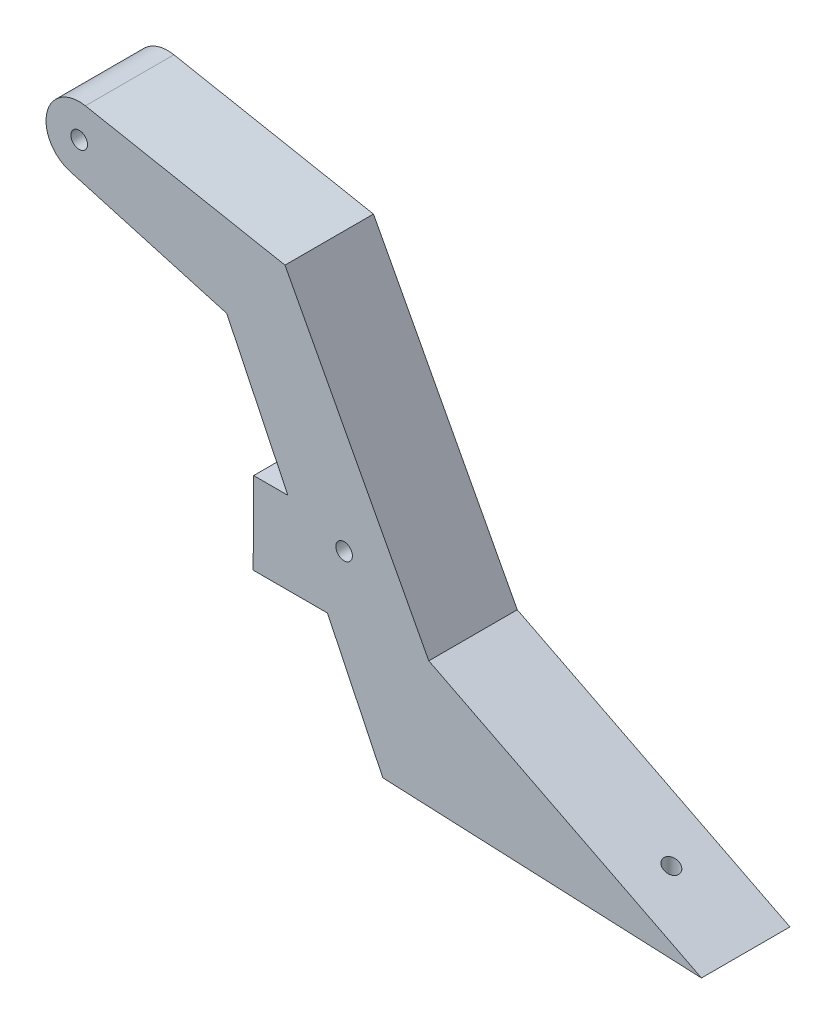
SolidWorks part; units mm, degrees
ref_plane "Front" through (0, 0, 0) normal (0, 0, 1) x (1, 0, 0)
ref_plane "Top" through (0, 0, 0) normal (0, 1, 0) x (1, 0, 0)
ref_plane "Right" through (0, 0, 0) normal (1, 0, 0) x (0, 0, -1)
sketch "草图1" plane through (0, 0, 0) normal (0, 0, 1) x (1, 0, 0)
  line L0 (1.1264, 5.8933) -> (37.221, -1.0054)
  line L1 (26.6827, -13.8357) -> (49.9154, -64.8874)
  line L2 (112.5381, -75) -> (53.3306, -72.3919)
  line L3 (63.228, -49.9799) -> (112.5381, -75)
  line L4 (49.9154, -64.8874) -> (53.3306, -72.3919)
  line L7 (26.6827, -13.8357) -> (-1.6431, -5.7706)
  line L9 (37.221, -1.0054) -> (63.228, -49.9799)
  arc A0 (1.1264, 5.8933) -> (-1.6431, -5.7706) centre (0, 0) ccw
  circle A1 centre (0, 0) radius 1.5
extrude "凸台-拉伸1" add sketch "草图1" along normal blind 16
sketch "草图2" plane through (-3.0794, -69.907, 0) normal (-0.044, -0.999, 0) x (0.999, -0.044, 0)
  circle A1 centre (66, 8) radius 1.35
  circle A2 centre (102, 8) radius 1.35
  circle A3 centre (84, 8) radius 1.35
extrude "切除-拉伸1" cut sketch "草图2" against normal blind 10
sketch "草图3" plane through (0, 0, 16) normal (0, 0, 1) x (1, 0, 0)
  line L0 (26.6827, -13.8357) -> (54.9111, -72.4615)
  line L1 (53.3306, -72.3919) -> (112.5381, -75) construction
  line L2 (54.9111, -72.4615) -> (53.3306, -72.3919)
  line L3 (53.3306, -72.3919) -> (26.6827, -13.8357)
extrude "切除-拉伸2" cut sketch "草图3" against normal blind 33
sketch "草图4" plane through (0, 0, 16) normal (0, 0, 1) x (1, 0, 0)
  line L0 (37.7391, -36.7979) -> (31.5529, -36.7979)
  line L1 (54.9111, -72.4615) -> (26.6827, -13.8357) construction
  line L2 (44.8955, -51.6606) -> (31.4609, -51.6606)
  line L3 (31.5529, -36.7979) -> (31.4609, -51.6606)
  line L4 (37.7391, -36.7979) -> (44.8955, -51.6606)
  line L5 (44.8955, -51.6606) -> (43.6725, -48.8252)
  point P1 (38.4039, -38.1788)
  point P8 (44.8955, -51.6606)
  point P9 (37.7391, -36.7979)
  line M1 (26.6827, -13.8357) -> (54.9111, -72.4615)
extrude "凸台-拉伸2" add sketch "草图4" against normal blind 16 contours L0 L3 L2 M1
sketch "草图5" plane through (0, 0, 16) normal (0, 0, 1) x (1, 0, 0)
  circle A0 centre (47.9111, -40.4615) radius 1.5
extrude "切除-拉伸3" cut sketch "草图5" against normal blind 24
sketch "草图7" plane through (31.7795, -0.1967, 0) normal (-1, 0.0062, 0) x (0, 0, 1)
  circle A0 centre (8, -44.016) radius 1.8
extrude "切除-拉伸5" cut sketch "草图7" against normal blind 10
